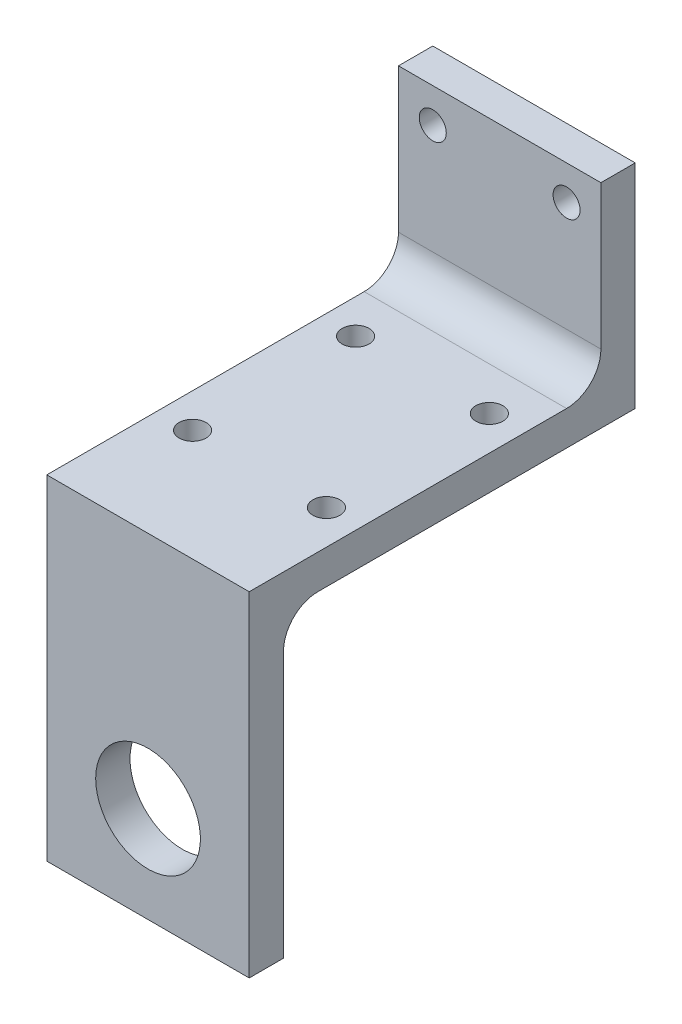
SolidWorks part; units mm, degrees
ref_plane "Front Plane" through (0, 0, 0) normal (0, 0, 1) x (1, 0, 0)
ref_plane "Top Plane" through (0, 0, 0) normal (0, 1, 0) x (1, 0, 0)
ref_plane "Right Plane" through (0, 0, 0) normal (1, 0, 0) x (0, 0, -1)
sketch "Sketch2" plane through (0, 0, 0) normal (1, 0, 0) x (0, 0, -1)
  line L3 (10.4198, -7.8348) -> (10.4198, 18.5812)
  line L4 (10.4198, 18.5812) -> (15.4998, 18.5812)
  line L5 (15.4998, 18.5812) -> (15.4998, -12.9148)
  line L6 (15.4998, -12.9148) -> (-41.6502, -12.9148)
  line L12 (10.4198, -7.8348) -> (-41.6502, -7.8348)
  line L13 (-41.6502, -7.8348) -> (-41.6502, -12.9148)
  line L15 (-41.6502, -12.9148) -> (-36.5702, -12.9148)
  line L16 (-41.6502, -12.9148) -> (-41.6502, -57.3648)
  line L17 (-41.6502, -57.3648) -> (-36.5702, -57.3648)
  line L18 (-36.5702, -12.9148) -> (-36.5702, -57.3648)
  dimension "D1" = 57.15
  dimension "D2" = 5.08
  dimension "D3" = 5.08
  dimension "D4" = 31.496
  dimension "D5" = 5.08
  dimension "D6" = 44.45
extrude "Boss-Extrude1" add sketch "Sketch2" along normal blind 29.972 contours L18 L6 L16 L17
fillet "Fillet1" radius 5.08 2 edges at (14.986, -7.8348, -10.4198) (14.986, -12.9148, 36.5702)
sketch "Sketch3" plane through (0, 0, -15.4998) normal (0, 0, -1) x (-1, 0, 0)
  line L2 (-29.972, 18.5812) -> (0, 18.5812) construction
  circle A0 centre (-24.892, 13.5012) radius 2
  circle A1 centre (-5.08, 13.5012) radius 2
  circle A2 centre (-5.08, -10.6288) radius 4
  circle A3 centre (-24.892, -10.6288) radius 4
  dimension "D1" = 5.08
  dimension "D4" = 4
  dimension "D5" = 4
  dimension "D6" = 8
  dimension "D7" = 8
  dimension "D2" = 5.08
  dimension "D3" = 5.08
  dimension "D8" = 24.13
extrude "Cut-Extrude1" cut sketch "Sketch3" against normal up to surface (5.08 mm away) up to face at (14.986, 7.9132, -10.4198)
sketch "Sketch4" plane through (0, -12.9148, 0) normal (0, -1, 0) x (1, 0, 0)
  line L3 (29.972, -15.4998) -> (29.972, 31.4902) construction
  line L4 (0, -15.4998) -> (0, 31.4902) construction
  circle A0 centre (24.892, 1.0102) radius 2
  circle A1 centre (5.08, 1.0102) radius 2
  circle A2 centre (24.892, 25.1402) radius 2
  circle A3 centre (5.08, 25.1402) radius 2
  dimension "D1" = 4
  dimension "D2" = 4
  dimension "D3" = 4
  dimension "D4" = 4
  dimension "D5" = 5.08
  dimension "D6" = 5.08
  dimension "D7" = 24.13
  dimension "D8" = 16.51
extrude "Cut-Extrude2" cut sketch "Sketch4" against normal blind 29.972
sketch "Sketch5" plane through (0, 0, 36.5702) normal (0, 0, -1) x (-1, 0, 0)
  line L0 (-29.972, -57.3648) -> (0, -57.3648) construction
  circle A0 centre (-14.986, -43.1408) radius 7.75
  point P2 (0, 0)
  point P5 (-14.986, -57.3648)
  dimension "D1" = 15.5
  dimension "D2" = 30.226
extrude "Cut-Extrude3" cut sketch "Sketch5" against normal up to surface (5.08 mm away) up to face at (14.986, -32.5998, 41.6502)
